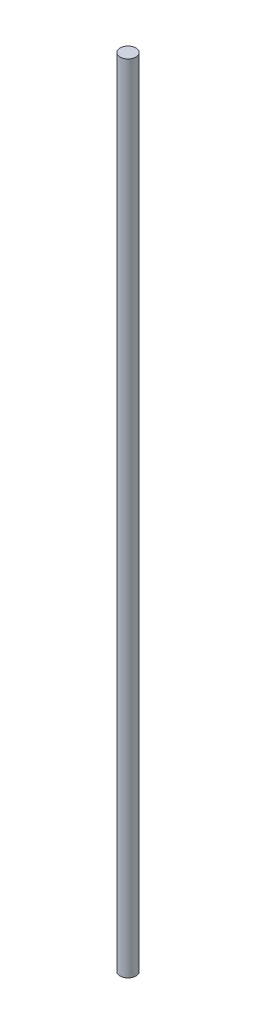
SolidWorks part; units mm, degrees
ref_plane "Front Plane" through (0, 0, 0) normal (0, 0, 1) x (1, 0, 0)
ref_plane "Top Plane" through (0, 0, 0) normal (0, 1, 0) x (1, 0, 0)
ref_plane "Right Plane" through (0, 0, 0) normal (1, 0, 0) x (0, 0, -1)
sketch "Sketch1" plane through (0, 0, 0) normal (0, 1, 0) x (1, 0, 0)
  circle A0 centre (0, 0) radius 4
  dimension "D1" = 8
extrude "Boss-Extrude1" add sketch "Sketch1" along normal blind 400 contours A0
